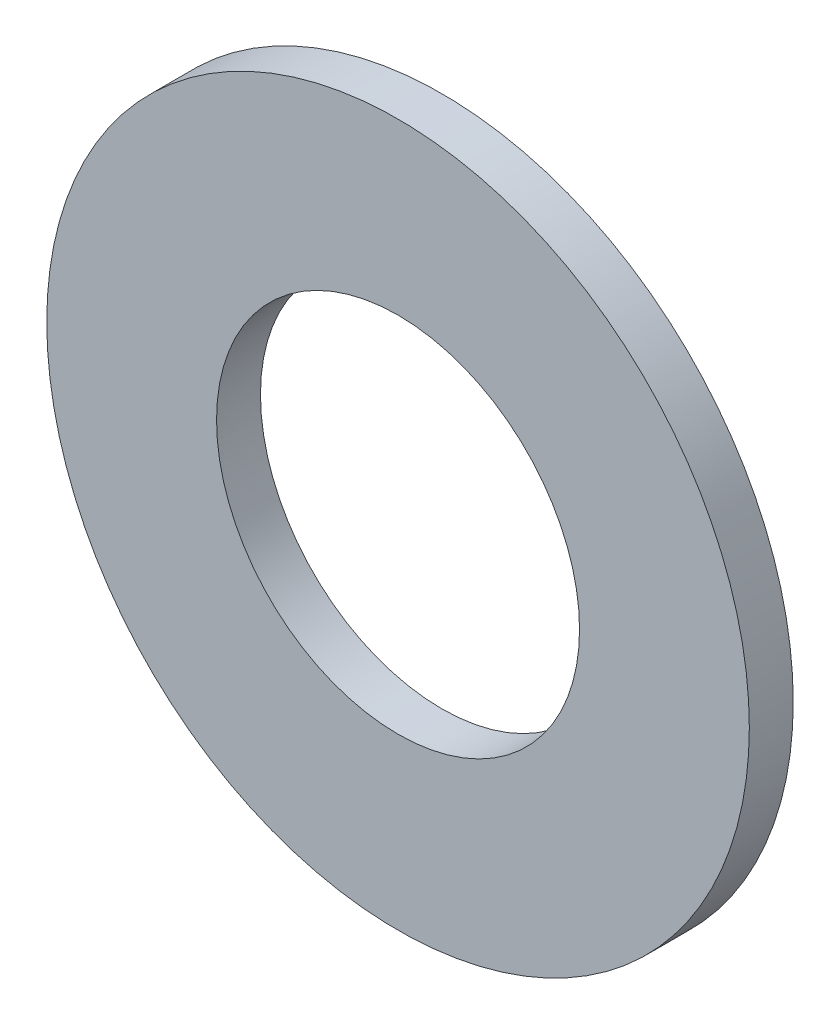
SolidWorks part; units mm, degrees
ref_plane "Front Plane" through (0, 0, 0) normal (0, 0, 1) x (1, 0, 0)
ref_plane "Top Plane" through (0, 0, 0) normal (0, 1, 0) x (1, 0, 0)
ref_plane "Right Plane" through (0, 0, 0) normal (1, 0, 0) x (0, 0, -1)
sketch "Sketch1" plane through (0, 0, 0) normal (0, 0, 1) x (1, 0, 0)
  circle A0 centre (0, 0) radius 6
  circle A1 centre (0, 0) radius 3.1
  dimension "D1" = 6.2
  dimension "D2" = 12
extrude "Boss-Extrude1" add sketch "Sketch1" along normal blind 0.75
